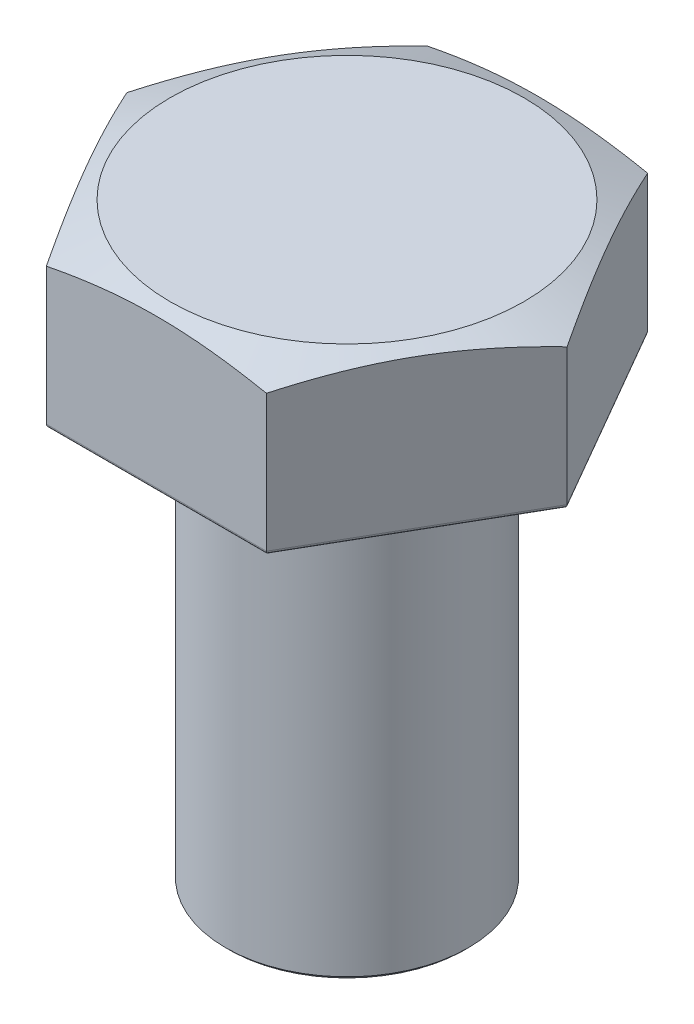
SolidWorks part; units mm, degrees
material "AISI 304"
ref_plane "前视基准面" through (0, 0, 0) normal (0, 0, 1) x (1, 0, 0)
ref_plane "上视基准面" through (0, 0, 0) normal (0, 1, 0) x (1, 0, 0)
ref_plane "右视基准面" through (0, 0, 0) normal (1, 0, 0) x (0, 0, -1)
sketch "草图1" plane through (0, 0, 0) normal (0, 1, 0) x (1, 0, 0)
  line L1 (12.7017, 0) -> (6.3509, 11)
  line L2 (6.3509, 11) -> (-6.3509, 11)
  line L3 (-6.3509, 11) -> (-12.7017, 0)
  line L4 (-12.7017, 0) -> (-6.3509, -11)
  line L5 (-6.3509, -11) -> (6.3509, -11)
  line L6 (6.3509, -11) -> (12.7017, 0)
  circle A0 centre (0, 0) radius 11 construction
  dimension "D1" = 22
extrude "凸台-拉伸1" add sketch "草图1" along normal blind 9.09
sketch "草图2" plane through (0, 0, 0) normal (0, -1, 0) x (1, 0, 0)
  circle A0 centre (0, 0) radius 7
  dimension "D1" = 14
extrude "凸台-拉伸2" add sketch "草图2" along normal blind 25
cosmetic thread "装饰螺纹线1" parameters "D2"=11.835
chamfer "倒角1" distance 0.2 angle 45 2 edges at (0, -25, -7) (0, 0, -7)
fillet "圆角1" radius 0.2 7 edges at (9.5263, 0, -5.5) (0, 0, -11) (-9.5263, 0, -5.5) (-9.5263, 0, 5.5) (0, 0, 11) (9.5263, 0, 5.5) (0, 0, 7.2)
sketch "草图3" plane through (0, 0, 0) normal (0, 0, 1) x (1, 0, 0)
  line L0 (0, 0) -> (0, 9.09) construction
  line L1 (-6.3509, 9.09) -> (6.3509, 9.09) construction
  line L2 (0, 9.09) -> (12.7017, 9.09) construction
  line L3 (10.2017, 9.09) -> (12.7017, 9.09)
  line L4 (12.7017, 9.09) -> (12.7017, 8.09)
  line L5 (12.7017, 9.09) -> (12.7017, 0.2) construction
  line L6 (12.7017, 8.09) -> (10.2017, 9.09)
  dimension "D1" = 2.5
  dimension "D2" = 1
revolve "切除-旋转1" cut sketch "草图3" angle 360 about L0
